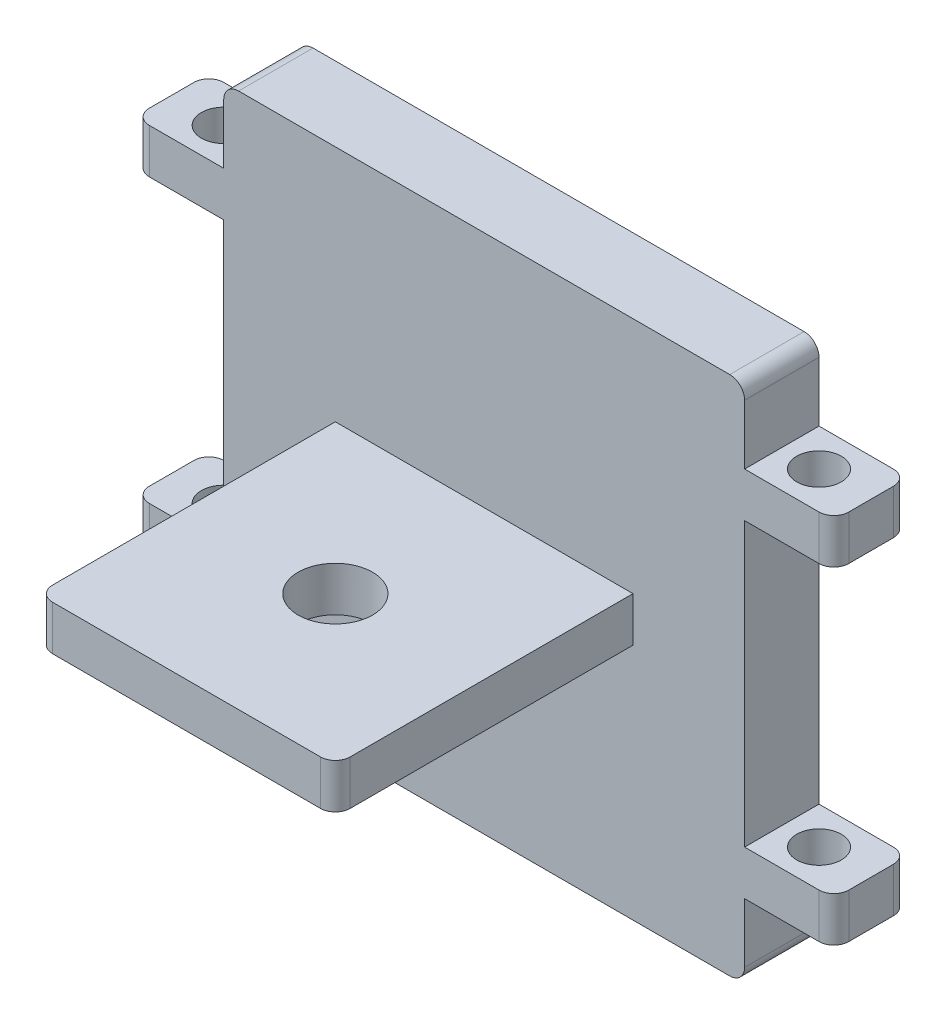
SolidWorks part; units mm, degrees
ref_plane "Front Plane" through (0, 0, 0) normal (0, 0, 1) x (1, 0, 0)
ref_plane "Top Plane" through (0, 0, 0) normal (0, 1, 0) x (1, 0, 0)
ref_plane "Right Plane" through (0, 0, 0) normal (1, 0, 0) x (0, 0, -1)
sketch "Sketch1" plane through (0, 0, 0) normal (0, 0, 1) x (1, 0, 0)
  line L0 (-13.347, 0) -> (21.653, 0)
  line L1 (21.653, 0) -> (21.653, 35)
  line L2 (21.653, 35) -> (-13.347, 35)
  line L3 (-13.347, 35) -> (-13.347, 0)
  dimension "D1" = 35
  dimension "D2" = 35
extrude "Boss-Extrude2" add sketch "Sketch1" along normal blind 5 contours L2 L3 L0 L1
sketch "Sketch2" plane through (21.653, 0, 0) normal (1, 0, 0) x (0, 0, -1)
  line L0 (-5, 30) -> (0, 30)
  line L1 (-5, 0) -> (-5, 35) construction
  line L2 (0, 0) -> (0, 35) construction
  line L3 (0, 30) -> (0, 27)
  line L4 (0, 27) -> (-5, 27)
  line L5 (-5, 27) -> (-5, 30)
  line L6 (-5, 8) -> (0, 8)
  line L7 (0, 8) -> (0, 5)
  line L8 (0, 5) -> (-5, 5)
  line L9 (-5, 5) -> (-5, 8)
  line L10 (-5, 35) -> (0, 35) construction
  line L11 (-5, 0) -> (0, 0) construction
  point P14 (0, 0)
  point P15 (-2.5, 27)
  dimension "D1" = 3
  dimension "D2" = 8
  dimension "D3" = 3
  dimension "D4" = 8
extrude "Boss-Extrude3" add sketch "Sketch2" along normal blind 6 and the other way blind 41
fillet "Fillet1" radius 1 8 edges at (-19.347, 6.5, 5) (-19.347, 6.5, 0) (-19.347, 28.5, 5) (-19.347, 28.5, 0) (27.653, 6.5, 5) (27.653, 6.5, 0) (27.653, 28.5, 5) (27.653, 28.5, 0)
sketch "Sketch3" plane through (0, 0, 0) normal (0, 1, 0) x (1, 0, 0)
  line L0 (4.153, 11.757) -> (4.153, -17.3212) construction
  line L2 (21.653, -5) -> (-13.347, -5) construction
  line L3 (21.653, 0) -> (-13.347, 0) construction
  line L4 (-18.347, -5) -> (-13.347, -5) construction
  line L5 (21.653, -5) -> (26.653, -5) construction
  point P4 (-15.847, -2.5)
  point P5 (24.153, -2.5)
  dimension "D1" = 20
  dimension "D2" = 5
  dimension "D3" = 2.5
  dimension "D4" = 2.5
  dimension "D5" = 20
hole_wizard "Ø3.0mm Dowel Hole1" positions "Sketch3" profile "Sketch5" hole size "Ø3.0" standard "ANSI Metric" end condition through all
sketch "Sketch5" plane through (24.153, 0, 2.5) normal (1, 0, 0) x (0, 0, -1)
  line L0 (0, 0) -> (0, 35)
  line L1 (0, 35) -> (1.5, 35)
  line L2 (1.5, 35) -> (1.5, 0)
  line L5 (1.5, 0) -> (0, 0)
  line L11 (0, -6.35) -> (0, 107.95) construction
  dimension "Thru Hole Dia." = 3
  dimension "Thru Hole Depth" = 35
sketch "Sketch6" plane through (0, 0, 5) normal (0, 0, 1) x (1, 0, 0)
  line L0 (4.153, 38.6181) -> (4.153, -5.4739) construction
  line L1 (-13.347, 27) -> (-13.347, 8) construction
  line L2 (-5.847, 19) -> (14.153, 19)
  line L3 (14.153, 19) -> (14.153, 16)
  line L4 (14.153, 16) -> (-5.847, 16)
  line L5 (-5.847, 16) -> (-5.847, 19)
  line L6 (21.653, 35) -> (-13.347, 35) construction
  point P6 (4.153, 19)
  dimension "D1" = 17.5
  dimension "D2" = 20
  dimension "D3" = 3
  dimension "D4" = 16
extrude "Boss-Extrude4" add sketch "Sketch6" along normal blind 20
sketch "Sketch7" plane through (0, 0, 0) normal (0, 1, 0) x (1, 0, 0)
  line L1 (14.153, -5) -> (-5.847, -5) construction
  line L2 (-5.847, -25) -> (-5.847, -5) construction
  point P0 (4.153, -15)
  dimension "D1" = 10
  dimension "D2" = 10
hole_wizard "Ø5.0mm Dowel Hole1" positions "Sketch7" profile "Sketch8" hole size "Ø5.0" standard "ANSI Metric" end condition through all
sketch "Sketch8" plane through (4.153, 0, 15) normal (1, 0, 0) x (0, 0, -1)
  line L0 (0, 0) -> (0, 35)
  line L1 (0, 35) -> (2.5, 35)
  line L2 (2.5, 35) -> (2.5, 0)
  line L5 (2.5, 0) -> (0, 0)
  line L11 (0, -6.35) -> (0, 107.95) construction
  dimension "Thru Hole Dia." = 5
  dimension "Thru Hole Depth" = 35
fillet "Fillet2" radius 1 2 edges at (14.153, 17.5, 25) (-5.847, 17.5, 25)
fillet "Fillet3" radius 1 4 edges at (21.653, 0, 2.5) (-13.347, 0, 2.5) (21.653, 35, 2.5) (-13.347, 35, 2.5)
